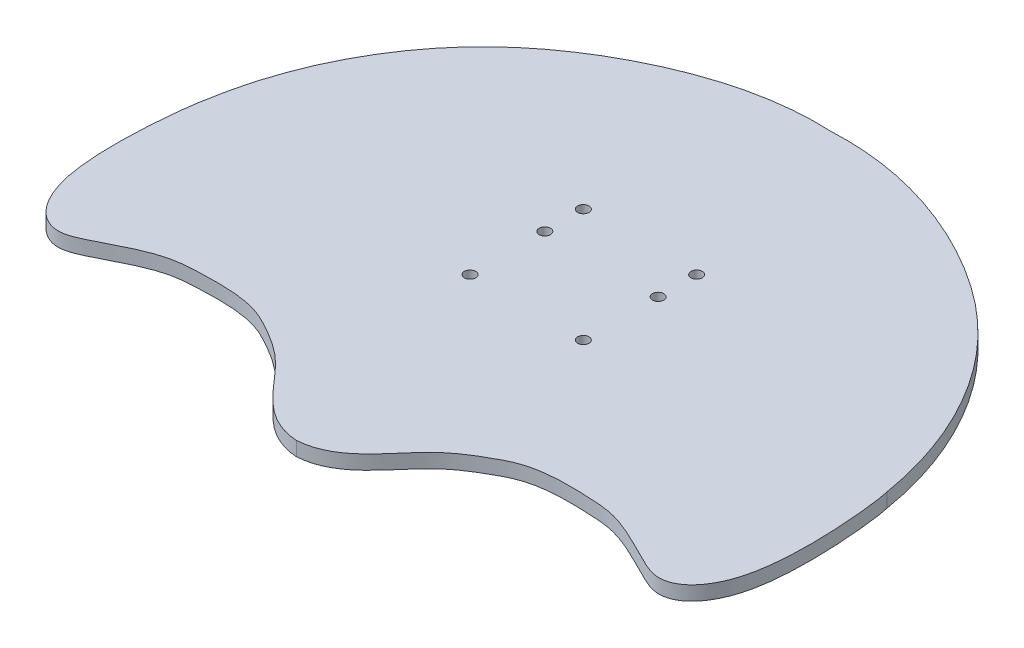
SolidWorks part; units mm, degrees
material "6061-T6 (SS)"
ref_plane "Front Plane" through (0, 0, 0) normal (0, 0, 1) x (1, 0, 0)
ref_plane "Top Plane" through (0, 0, 0) normal (0, 1, 0) x (1, 0, 0)
ref_plane "Right Plane" through (0, 0, 0) normal (1, 0, 0) x (0, 0, -1)
sketch "Sketch3" plane through (0, 0, 0) normal (0, 1, 0) x (1, 0, 0)
  line L0 (0, 0) -> (0, 159.1899) construction
  line L1 (0, 0) -> (0, -140.5301) construction
  line L2 (0, 0) -> (-190.5, 0) construction
  line L3 (0, 0) -> (190.5, 0) construction
  spline S0 degree 3 poles (-190.5, 0) (-184.3927, 37.537) (-157.2613, 93.9641) (-82.3875, 146.6227) (-31.3114, 160.7999) (0, 159.1899) knots 0 0 0 0 0.424401 0.65637 1 1 1 1
  spline S1 degree 3 poles (-190.5, 0) (-192.064, -4.9635) (-201.9672, -83.3146) (-174.6966, -109.29) (-151.6301, -100.568) (-131.4108, -87.7198) (-96.8436, -85.3754) (-78.6925, -86.2588) (-58.8335, -96.8794) (-37.3059, -109.9358) (-21.3496, -139.1148) (0, -140.5301) knots 0 0 0 0 0.166997 0.292321 0.319633 0.426735 0.458914 0.609242 0.64191 0.766802 1 1 1 1
  spline S2 degree 3 poles (190.5, 0) (192.064, -4.9635) (201.9672, -83.3146) (174.6966, -109.29) (151.6301, -100.568) (131.4108, -87.7198) (96.8436, -85.3754) (78.6925, -86.2588) (58.8335, -96.8794) (37.3059, -109.9358) (21.3496, -139.1148) (0, -140.5301) knots 0 0 0 0 0.166997 0.292321 0.319633 0.426735 0.458914 0.609242 0.64191 0.766802 1 1 1 1
  spline S3 degree 3 poles (190.5, 0) (184.3927, 37.537) (157.2613, 93.9641) (82.3875, 146.6227) (31.3114, 160.7999) (0, 159.1899) knots 0 0 0 0 0.424401 0.65637 1 1 1 1
  dimension "D1" = 381
  dimension "D2" = 299.72
  dimension "D3" = 159.1899
  dimension "D4" = 86.8953
  dimension "D5" = 104.4979
  dimension "D6" = 29.1616
  dimension "D7" = 92.2742
  dimension "D8" = 108.411
  dimension "D9" = 67.4883
  dimension "D10" = 43.7314
  dimension "D11" = 117.6915
  dimension "D12" = 162.2568
  dimension "D13" = 89.4522
  dimension "D14" = 140.1036
  dimension "D15" = 175.0666
  dimension "D16" = 50.2669
  dimension "D17" = 101.3666
  dimension "D18" = 138.1225
  dimension "D19" = 155.1557
  dimension "D20" = 192.0074
  dimension "D21" = 193.9268
  dimension "D23" = 76.6666
extrude "Boss-Extrude1" add sketch "Sketch3" along normal blind 7.9502 from surface at 0 starting at plane "Top Plane"
sketch "Sketch5" plane through (0, 0, 0) normal (0, -1, 0) x (1, 0, 0)
  line L0 (0, 0) -> (0, -20.32) construction
  line L1 (31.75, -52.07) -> (-31.75, -52.07)
  line L2 (31.75, -52.07) -> (31.75, 11.43)
  line L3 (31.75, 11.43) -> (-31.75, 11.43)
  line L4 (-31.75, -52.07) -> (-31.75, 11.43)
  line L5 (31.75, -52.07) -> (-31.75, 11.43) construction
  line L6 (31.75, 11.43) -> (-31.75, -52.07) construction
  line L7 (-31.75, -52.07) -> (-31.75, -30.48)
  line L8 (-31.75, -30.48) -> (31.75, -30.48) construction
  point P0 (0, -20.32)
  point P3 (0, -20.32)
  dimension "D2" = 63.5
  dimension "D3" = 63.5
  dimension "D4" = 21.59
hole_wizard "1/4 (0.25) Diameter Hole1" positions "Sketch6" profile "Sketch7" hole size "1/4" standard "ANSI Inch" end condition through all
sketch "Sketch6" plane through (0, 0, 0) normal (0, -1, 0) x (-1, 0, 0)
  point P0 (-31.75, 52.07)
  point P3 (31.75, 52.07)
  point P6 (31.75, -11.43)
  point P9 (-31.75, -11.43)
  point P12 (-31.75, 30.48)
  point P15 (31.75, 30.48)
sketch "Sketch7" plane through (31.75, 0, -52.07) normal (1, 0, 0) x (0, 0, -1)
  line L0 (0, 0) -> (0, 7.9502)
  line L1 (0, 7.9502) -> (3.175, 7.9502)
  line L2 (3.175, 7.9502) -> (3.175, 0)
  line L5 (3.175, 0) -> (0, 0)
  line L11 (0, -6.35) -> (0, 107.95) construction
  dimension "Thru Hole Dia." = 6.35
  dimension "Thru Hole Depth" = 7.9502
sketch "Sketch9" [suppressed] plane through (0, 7.9502, 0) normal (0, 1, 0) x (1, 0, 0)
  line L0 (102.3823, -86.0787) -> (102.3823, 130.9193)
  line L1 (-50.7649, -102.4301) -> (50.7649, -102.4301)
  spline S0 degree 3 poles (0, -140.5301) (21.3496, -139.1148) (37.3059, -109.9358) (58.8335, -96.8794) (78.6925, -86.2588) (96.8436, -85.3754) (131.4108, -87.7198) (151.6301, -100.568) (174.6966, -109.29) (201.9672, -83.3146) (192.064, -4.9635) (190.5, 0) knots 0 0 0 0 0.233198 0.35809 0.390758 0.541086 0.573265 0.680367 0.707679 0.833003 1 1 1 1 construction
  spline S1 degree 3 poles (190.5, 0) (184.3927, 37.537) (157.2613, 93.9641) (82.3875, 146.6227) (31.3114, 160.7999) (0, 159.1899) knots 0 0 0 0 0.424401 0.65637 1 1 1 1 construction
  spline S2 degree 3 poles (-190.5, 0) (-192.064, -4.9635) (-201.9672, -83.3146) (-174.6966, -109.29) (-151.6301, -100.568) (-131.4108, -87.7198) (-96.8436, -85.3754) (-78.6925, -86.2588) (-58.8335, -96.8794) (-37.3059, -109.9358) (-21.3496, -139.1148) (0, -140.5301) knots 0 0 0 0 0.166997 0.292321 0.319633 0.426735 0.458914 0.609242 0.64191 0.766802 1 1 1 1 construction
  dimension "D1" = 38.1
split line "Split Line1" [suppressed]
equation "\"Plate thickness\"=0.313"
equation "\"D1@Boss-Extrude1\"=\"Plate thickness\""
equation "\"Bracket Alignment\"= .80"
equation "\"D1@Sketch5\"=\"Bracket Alignment\""
